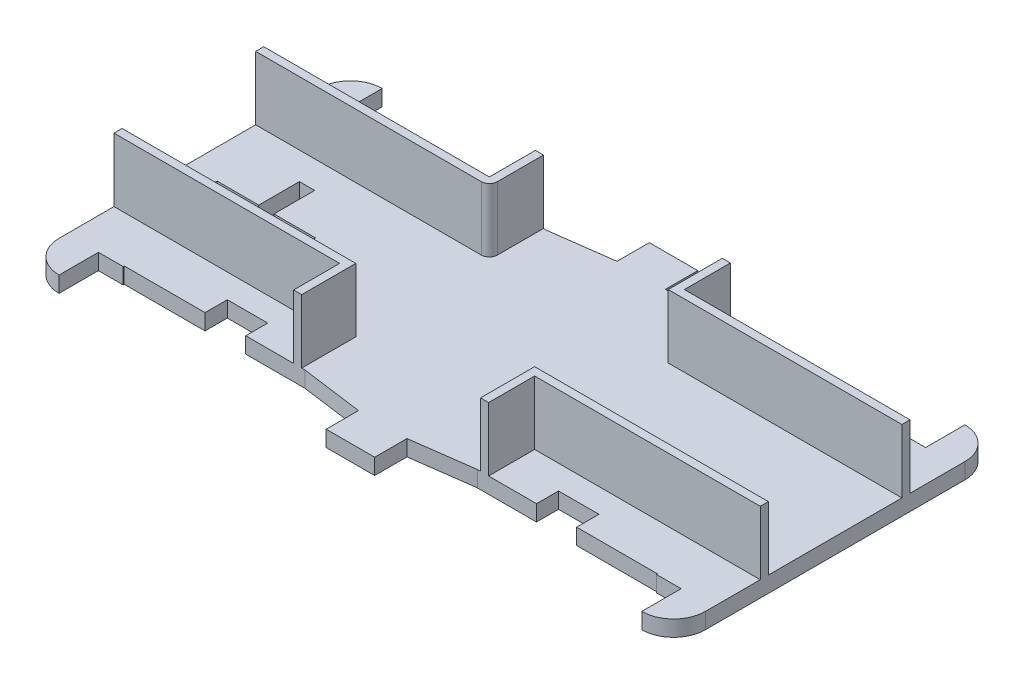
SolidWorks part; units mm, degrees
ref_plane "Front Plane" through (0, 0, 0) normal (0, 0, 1) x (1, 0, 0)
ref_plane "Top Plane" through (0, 0, 0) normal (0, 1, 0) x (1, 0, 0)
ref_plane "Right Plane" through (0, 0, 0) normal (1, 0, 0) x (0, 0, -1)
sketch "Sketch1" plane through (0, 0, 0) normal (0, 1, 0) x (1, 0, 0)
  line L1 (101.6, -50.8) -> (-101.6, -50.8)
  line L2 (101.6, -50.8) -> (101.6, 50.8)
  line L3 (101.6, 50.8) -> (-101.6, 50.8)
  line L4 (-101.6, -50.8) -> (-101.6, 50.8)
  line L5 (101.6, -50.8) -> (-101.6, 50.8) construction
  line L6 (101.6, 50.8) -> (-101.6, -50.8) construction
  point P0 (0, 0)
  dimension "D1" = 101.6
  dimension "D2" = 203.2
extrude "Boss-Extrude1" add sketch "Sketch1" along normal blind 5
sketch "Sketch2" plane through (0, 5, 0) normal (0, 1, 0) x (1, 0, 0)
  line L0 (-83.82, 50.8) -> (-83.82, 38.1)
  line L1 (101.6, 50.8) -> (-101.6, 50.8) construction
  line L2 (-83.82, 38.1) -> (-58.42, 38.1)
  line L3 (-58.42, 38.1) -> (-58.42, 31.0929)
  line L4 (-58.42, 31.0929) -> (-45.72, 31.0929)
  line L5 (-45.72, 31.0929) -> (-45.72, 38.0123)
  line L6 (-45.72, 38.0123) -> (-27.1086, 38.0123)
  line L7 (-27.1086, 38.0123) -> (-7.62, 40.64)
  line L8 (-7.62, 40.64) -> (-7.62, 50.8)
  line L9 (-7.62, 50.8) -> (-7.62, 63.5)
  line L10 (-7.62, 63.5) -> (-83.82, 63.5)
  line L11 (-83.82, 63.5) -> (-83.82, 50.8)
  line L12 (-101.6, 50.8) -> (-101.6, -50.8) construction
  dimension "D1" = 12.7
  dimension "D2" = 10.16
  dimension "D3" = 12.7
  dimension "D4" = 76.2
  dimension "D5" = 25.4
  dimension "D6" = 12.7
  dimension "D7" = 18.6114
  dimension "D8" = 17.78
extrude "Cut-Extrude1" cut sketch "Sketch2" against normal through all
mirror "Mirror2" about plane through (0, 0, 0) normal (0, 0, 1) of "Cut-Extrude1"
mirror "Mirror3" about plane through (0, 0, 0) normal (1, 0, 0) of "Mirror2" second plane through (0, 0, 0) second plane normal (0, 1, 0)
fillet "Fillet1" radius 10 4 edges at (101.6, 2.5, -50.8) (101.6, 2.5, 50.8) (-101.6, 2.5, 50.8) (-101.6, 2.5, -50.8)
sketch "Sketch4" plane through (0, 5, 0) normal (0, 1, 0) x (1, 0, 0)
  line L0 (-79.2536, -0.3862) -> (-92.3307, -0.3862)
  line L1 (-79.2536, -18.0652) -> (-74.4507, -18.0652)
  line L2 (-79.2536, -18.0652) -> (-79.2536, -5.2643)
  line L3 (-79.2536, 12.4148) -> (-74.4507, 12.4148)
  line L4 (-74.4507, -18.0652) -> (-74.4507, -5.2643)
  line L5 (-79.2536, -0.3862) -> (-79.2536, 12.4148)
  line L7 (-61.3735, -5.2643) -> (-74.4507, -5.2643)
  line L8 (-61.3735, -5.2643) -> (-61.3735, -0.3862)
  line L9 (-61.3735, -0.3862) -> (-74.4507, -0.3862)
  line L10 (-92.3307, -5.2643) -> (-92.3307, -0.3862)
  line L15 (-79.2536, -5.2643) -> (-92.3307, -5.2643)
  line L18 (-74.4507, -0.3862) -> (-74.4507, 12.4148)
  point P0 (-76.8521, -2.8252)
  point P5 (-76.6599, -4.0448)
  dimension "D1" = 30.48
  dimension "D2" = 30.9571
extrude "Cut-Extrude4" cut sketch "Sketch4" against normal through all
sketch "Sketch5" plane through (0, 5, 0) normal (0, 1, 0) x (1, 0, 0)
  line L0 (-101.6, 23.5395) -> (-30.6562, 23.5395)
  line L1 (-101.6, 40.8) -> (-101.6, -40.8) construction
  line L2 (-30.6562, 23.5395) -> (-30.6562, 38.0123)
  line L3 (-45.72, 38.0123) -> (-27.1086, 38.0123) construction
extrude "Extrude-Thin2" add sketch "Sketch5" along normal blind 20 thin
fillet "Fillet2" radius 2.54 1 edges at (-28.1162, 15, -20.9995)
mirror "Mirror4" about plane through (0, 0, 0) normal (0, 0, 1) of "Extrude-Thin2"
mirror "Mirror5" about plane through (0, 0, 0) normal (1, 0, 0) of "Mirror4", "Extrude-Thin2"
sketch "Sketch6" plane through (0, 5, 0) normal (0, 1, 0) x (1, 0, 0)
  line L0 (-91.6, 50.8) -> (-91.6, 38.4297)
  line L1 (-91.6, 38.4297) -> (-83.82, 38.4297)
  line L2 (-83.82, 38.4297) -> (-83.82, 50.8)
  line L3 (-83.82, 50.8) -> (-91.6, 50.8) construction
  line L4 (-83.82, 50.8) -> (-83.82, 38.1) construction
  line L5 (-83.82, 50.8) -> (-91.6, 50.8)
extrude "Cut-Extrude5" cut sketch "Sketch6" against normal through all
mirror "Mirror6" about plane through (0, 0, 0) normal (0, 0, 1) of "Cut-Extrude5"
mirror "Mirror7" about plane through (0, 0, 0) normal (1, 0, 0) of "Mirror6", "Cut-Extrude5"
equation "\"0.15inin\"=0.1"
